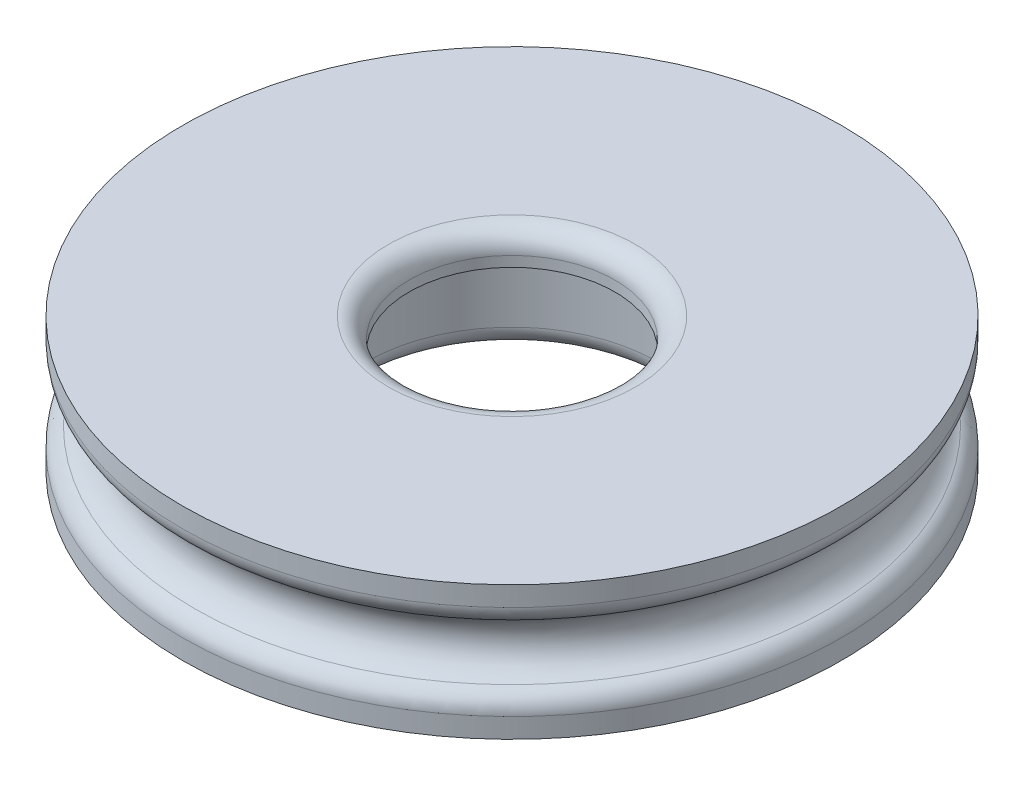
SolidWorks part; units mm, degrees
ref_plane "Front Plane" through (0, 0, 0) normal (0, 0, 1) x (1, 0, 0)
ref_plane "Top Plane" through (0, 0, 0) normal (0, 1, 0) x (1, 0, 0)
ref_plane "Right Plane" through (0, 0, 0) normal (1, 0, 0) x (0, 0, -1)
sketch "Sketch1" plane through (0, 0, 0) normal (0, 1, 0) x (1, 0, 0)
  circle A2 centre (0, 0) radius 3.55
  circle A3 centre (0, 0) radius 8
  dimension "D1" = 7.1
  dimension "D2" = 16
extrude "Boss-Extrude1" add sketch "Sketch1" along normal mid plane 3.25
sketch "Sketch2" plane through (0, 0, 0) normal (1, 0, 0) x (0, 0, -1)
  line L0 (-8, -1.625) -> (-8, -0.75) construction
  line L1 (-8, 1.625) -> (-8, -1.625) construction
  line L2 (-8, 1.625) -> (-8, 0.75) construction
  line L3 (-8, 0.75) -> (-8, -0.75)
  line L4 (-8, -1.625) -> (8, -1.625) construction
  line L5 (-8, 0) -> (-7.25, 0) construction
  ellipse E0 centre (-8, 0) end of major axis (-7.25, 0) minor radius 0.75 (-8, -0.75) -> (-8, 0.75) ccw
  dimension "D1" = 1.5
  dimension "D2" = 0.75
  dimension "D3" = 0.875
revolve "Cut-Revolve1" cut sketch "Sketch2" angle 360 about axis through (0, 1.625, 0) along (0, -1, 0)
sketch "Sketch3" plane through (0, 1.625, 0) normal (0, 1, 0) x (1, 0, 0)
  circle A0 centre (0, 0) radius 4
  circle A1 centre (0, 0) radius 2.5
  dimension "D1" = 5
  dimension "D2" = 8
extrude "Boss-Extrude2" add sketch "Sketch3" against normal blind 0.75
fillet "Fillet1" radius 0.5 5 edges at (0, -1.625, 3.55) (0, 0.875, 3.55) (0, 0.75, 8) (0, -0.75, 8) (0, 1.625, 2.5)
